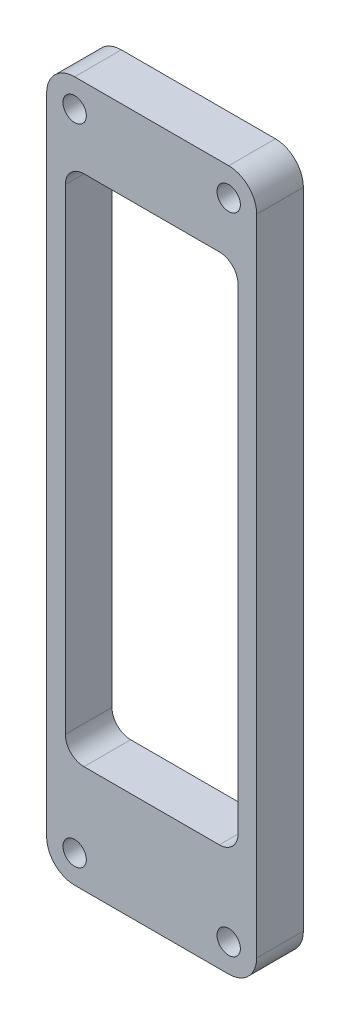
SolidWorks part; units mm, degrees
ref_plane "Front Plane" through (0, 0, 0) normal (0, 0, 1) x (1, 0, 0)
ref_plane "Top Plane" through (0, 0, 0) normal (0, 1, 0) x (1, 0, 0)
ref_plane "Right Plane" through (0, 0, 0) normal (1, 0, 0) x (0, 0, -1)
sketch "Sketch1" plane through (0, 0, 0) normal (0, 0, 1) x (1, 0, 0)
  line L1 (-19.2632, 110.1316) -> (13.7368, 110.1316)
  line L2 (-25.2632, 104.1316) -> (-25.2632, -33.8684)
  line L3 (-19.2632, -39.8684) -> (13.7368, -39.8684)
  line L4 (19.7368, 104.1316) -> (19.7368, -33.8684)
  arc A0 (19.7368, -33.8684) -> (13.7368, -39.8684) centre (13.7368, -33.8684) cw
  arc A1 (-19.2632, -39.8684) -> (-25.2632, -33.8684) centre (-19.2632, -33.8684) cw
  arc A2 (19.7368, 104.1316) -> (13.7368, 110.1316) centre (13.7368, 104.1316) ccw
  arc A3 (-19.2632, 110.1316) -> (-25.2632, 104.1316) centre (-19.2632, 104.1316) ccw
  circle A4 centre (-19.2632, 104.1316) radius 2.5
  circle A5 centre (13.7368, 104.1316) radius 2.5
  circle A6 centre (-19.2632, -33.8684) radius 2.5
  circle A7 centre (13.7368, -33.8684) radius 2.5
  point P6 (19.7368, -39.8684)
  point P9 (-25.2632, -39.8684)
  point P14 (-25.2632, 110.1316)
  dimension "D3" = 6
  dimension "D4" = 5
  dimension "D5" = 5
  dimension "D6" = 5
  dimension "D7" = 5
  dimension "D1" = 45
  dimension "D2" = 150
extrude "Boss-Extrude1" add sketch "Sketch1" along normal blind 10
sketch "Sketch2" plane through (0, 0, 10) normal (0, 0, 1) x (1, 0, 0)
  line L0 (19.7368, -33.8684) -> (19.7368, 104.1316) construction
  line L1 (-17.2632, 93.1316) -> (11.7368, 93.1316)
  line L2 (-21.2632, 89.1316) -> (-21.2632, -12.8684)
  line L3 (-17.2632, -16.8684) -> (11.7368, -16.8684)
  line L4 (15.7368, 89.1316) -> (15.7368, -12.8684)
  line L5 (-25.2632, 104.1316) -> (-25.2632, -33.8684) construction
  line L6 (13.7368, 110.1316) -> (-19.2632, 110.1316) construction
  line L7 (-19.2632, -39.8684) -> (13.7368, -39.8684) construction
  arc A0 (-21.2632, -12.8684) -> (-17.2632, -16.8684) centre (-17.2632, -12.8684) ccw
  arc A1 (11.7368, -16.8684) -> (15.7368, -12.8684) centre (11.7368, -12.8684) ccw
  arc A2 (15.7368, 89.1316) -> (11.7368, 93.1316) centre (11.7368, 89.1316) ccw
  arc A3 (-21.2632, 89.1316) -> (-17.2632, 93.1316) centre (-17.2632, 89.1316) cw
  dimension "D5" = 4
  dimension "D1" = 4
  dimension "D2" = 4
  dimension "D3" = 17
  dimension "D4" = 23
extrude "Cut-Extrude1" cut sketch "Sketch2" against normal blind 10
